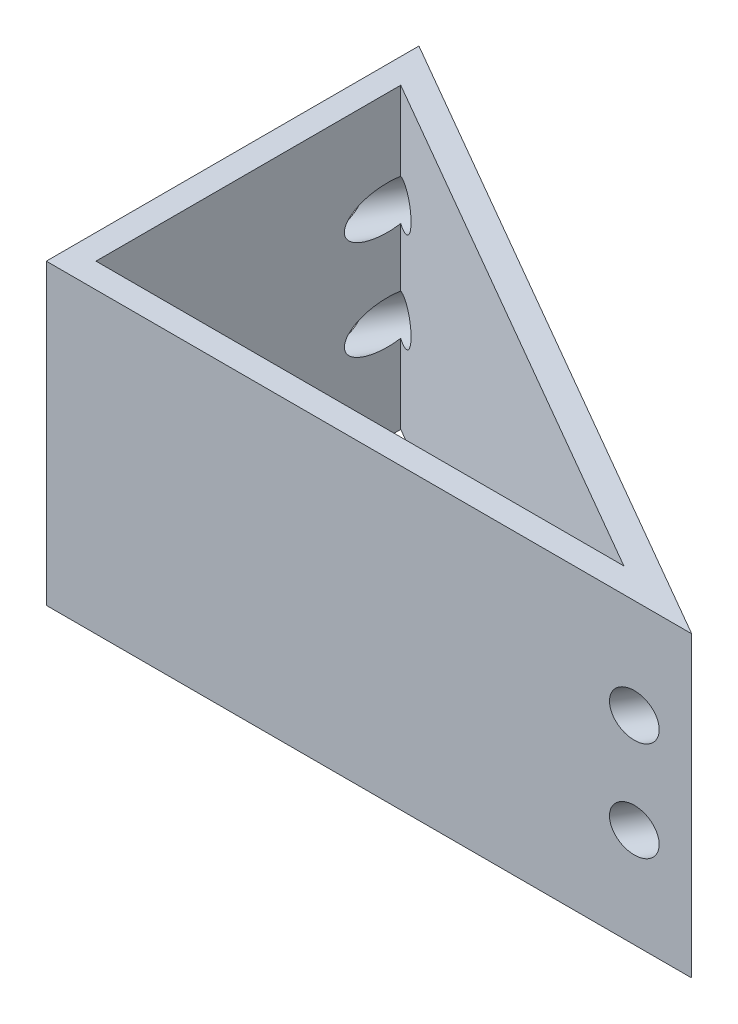
SolidWorks part; units mm, degrees
material "6061 Alloy"
ref_plane "Front Plane" through (0, 0, 0) normal (0, 0, 1) x (1, 0, 0)
ref_plane "Top Plane" through (0, 0, 0) normal (0, 1, 0) x (1, 0, 0)
ref_plane "Right Plane" through (0, 0, 0) normal (1, 0, 0) x (0, 0, -1)
sketch "Sketch1" plane through (0, 0, 0) normal (0, 1, 0) x (1, 0, 0)
  line L0 (0, 0) -> (0, 47.625)
  line L1 (0, 47.625) -> (82.4889, 0)
  line L2 (82.4889, 0) -> (0, 0)
  dimension "D1" = 30
  dimension "D2" = 95.25
extrude "Boss-Extrude1" add sketch "Sketch1" along normal blind 38.1
sketch "Sketch2" plane through (0, 38.1, 0) normal (0, 1, 0) x (1, 0, 0)
  line L6 (3.175, 3.175) -> (70.6397, 3.175)
  line L7 (70.6397, 3.175) -> (3.175, 42.1257)
  line L8 (3.175, 42.1257) -> (3.175, 3.175)
  line L9 (3.175, 3.175) -> (70.6397, 3.175)
  line L10 (70.6397, 3.175) -> (3.175, 42.1257)
  line L11 (3.175, 42.1257) -> (3.175, 3.175)
  dimension "D1" = 3.175
extrude "Cut-Extrude1" cut sketch "Sketch2" against normal through all
sketch "Sketch3" plane through (20.6222, 0, -35.7187) normal (0.5, 0, -0.866) x (-0.866, 0, -0.5)
  line L1 (-71.4375, 38.1) -> (23.8125, 38.1) construction
  line L4 (-71.4375, 38.1) -> (-71.4375, 0) construction
  line L5 (23.8125, 38.1) -> (23.8125, 0) construction
  point P0 (17.4625, 12.7)
  point P1 (-65.0875, 25.4)
  point P8 (17.4625, 25.4)
  point P9 (-65.0875, 12.7)
  dimension "D1" = 6.35
  dimension "D2" = 25.4
  dimension "D3" = 6.35
  dimension "D4" = 12.7
hole_wizard "M5 Clearance Hole1" positions "Sketch4" profile "Sketch5" hole size "M5" standard "ANSI Metric" end condition through all
sketch "Sketch4" plane through (20.6222, 0, -35.7187) normal (0.5, 0, -0.866) x (-0.866, 0, -0.5)
  point P0 (17.4625, 12.7)
  point P3 (-65.0875, 12.7)
  point P7 (-65.0875, 25.4)
  point P10 (17.4625, 25.4)
sketch "Sketch5" plane through (5.4993, 12.7, -44.45) normal (0, 1, 0) x (-0.866, 0, -0.5)
  line L0 (0, 0) -> (0, 41.2445)
  line L1 (0, 41.2445) -> (2.75, 41.2445)
  line L2 (2.75, 41.2445) -> (2.75, 0)
  line L5 (2.75, 0) -> (0, 0)
  line L11 (0, -6.35) -> (0, 107.95) construction
  dimension "Thru Hole Dia." = 5.5
  dimension "Thru Hole Depth" = 41.2445
